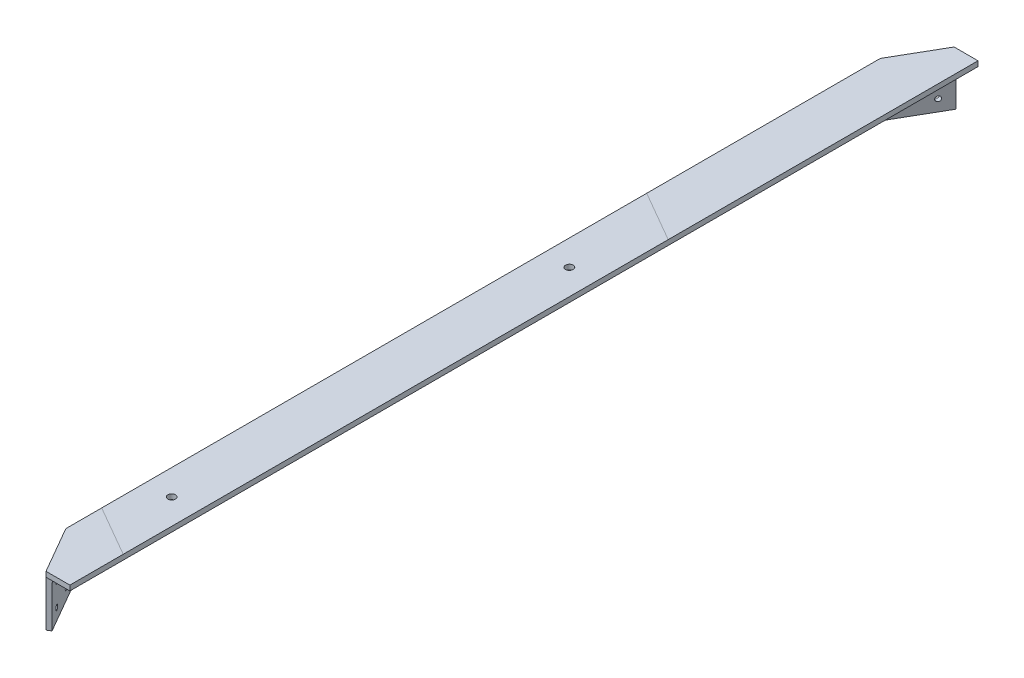
SolidWorks part; units mm, degrees
material "1.0116 (S235J2G3)"
ref_plane "Front Plane" through (0, 0, 0) normal (0, 0, 1) x (1, 0, 0)
ref_plane "Top Plane" through (0, 0, 0) normal (0, 1, 0) x (1, 0, 0)
ref_plane "Right Plane" through (0, 0, 0) normal (1, 0, 0) x (0, 0, -1)
sketch "Sketch1" plane through (0, 0, 0) normal (0, 0, 1) x (1, 0, 0)
  line L0 (-8, 8) -> (72, 8)
  line L1 (72, 8) -> (72, 0)
  line L2 (72, 0) -> (0, 0)
  line L3 (0, 0) -> (0, -72)
  line L4 (0, -72) -> (-8, -72)
  line L5 (-8, -72) -> (-8, 8)
  dimension "D1" = 80
  dimension "D2" = 80
  dimension "D3" = 8
  dimension "D4" = 8
extrude "Boss-Extrude1" add sketch "Sketch1" along normal blind 640
sketch "Sketch3" plane through (0, 0, 0) normal (0, 1, 0) x (1, 0, 0)
  line L0 (-8, -640) -> (34.5, -713.6122)
  line L1 (34.5, -713.6122) -> (72, -713.6122)
  line L2 (72, -713.6122) -> (72, -640)
  line L3 (72, -640) -> (-8, -640)
  line L4 (-8, -640) -> (-8, 0) construction
  dimension "D1" = 210
  dimension "D2" = 85
extrude "Boss-Extrude2" add sketch "Sketch3" along normal blind 8
sketch "Sketch4" plane through (0, 0, 0) normal (0, -1, 0) x (1, 0, 0)
  line L0 (-8, 640) -> (34.5, 713.6122)
  line L1 (34.5, 713.6122) -> (40.5, 710.1481)
  line L2 (40.5, 710.1481) -> (0, 640)
  line L3 (-8, 640) -> (0, 640) construction
  line L4 (0, 640) -> (-8, 640)
  dimension "D1" = 8
extrude "Boss-Extrude3" add sketch "Sketch4" along normal blind 72
sketch "Sketch6" plane through (-277.1281, 0, 160) normal (0.866, 0, -0.5) x (-0.5, 0, -0.866)
  line L0 (-635.2563, -36) -> (-554.2563, -36) construction
  line L1 (-635.2563, -72) -> (-635.2563, 0) construction
  line L2 (-554.2563, -72) -> (-554.2563, 0) construction
  line L3 (-594.7563, 0) -> (-594.7563, -72) construction
  line L4 (-554.2563, 0) -> (-635.2563, 0) construction
  line L5 (-554.2563, -72) -> (-635.2563, -72) construction
  circle A0 centre (-615.0063, -18) radius 4
  circle A1 centre (-574.5063, -18) radius 4
  circle A2 centre (-574.5063, -54) radius 4
  circle A3 centre (-615.0063, -54) radius 4
  dimension "D1" = 20.25
  dimension "D3" = 8
  dimension "D2" = 18
extrude "Cut-Extrude1" cut sketch "Sketch6" against normal blind 8
fillet "Fillet1" radius 10 2 edges at (-8, -32, 640) (0, -36, 640)
fillet "Fillet2" radius 8 3 edges at (0, 0, 318.6603) (0.3407, 0, 639.9087) (20.9199, 0, 676.2343)
mirror "Mirror1" about plane through (0, 0, 0) normal (0, 0, 1) of "Boss-Extrude1", "Boss-Extrude2", "Boss-Extrude3", "Cut-Extrude1", "Fillet1", "Fillet2"
sketch "Sketch7" plane through (0, 8, 0) normal (0, 1, 0) x (1, 0, 0)
  line L0 (72, -629.7622) -> (-8, -583.5741)
  line L1 (72, -713.6122) -> (72, 713.6122) construction
  line L2 (-8, -637.3205) -> (-8, 637.3205) construction
  line L3 (-8, -583.5741) -> (-8, 272.9502)
  line L4 (-8, 272.9502) -> (72, 226.7622)
  line L5 (72, 226.7622) -> (72, -629.7622)
  dimension "D1" = 60
  dimension "D2" = 83.85
  dimension "D3" = 486.85
split line "Split Line1"
sketch "Sketch8" plane through (0, 8, 0) normal (0, 1, 0) x (1, 0, 0)
  line L0 (34.5, -713.6122) -> (72, -713.6122) construction
  line L1 (72, -629.7622) -> (72, 226.7622) construction
  circle A0 centre (32, 111.3878) radius 6
  circle A1 centre (32, -513.6122) radius 6
  dimension "D1" = 825
  dimension "D3" = 12
  dimension "D4" = 12
  dimension "D6" = 40
  dimension "D2" = 200
  dimension "D5" = 40
extrude "Cut-Extrude2" cut sketch "Sketch8" against normal blind 8
